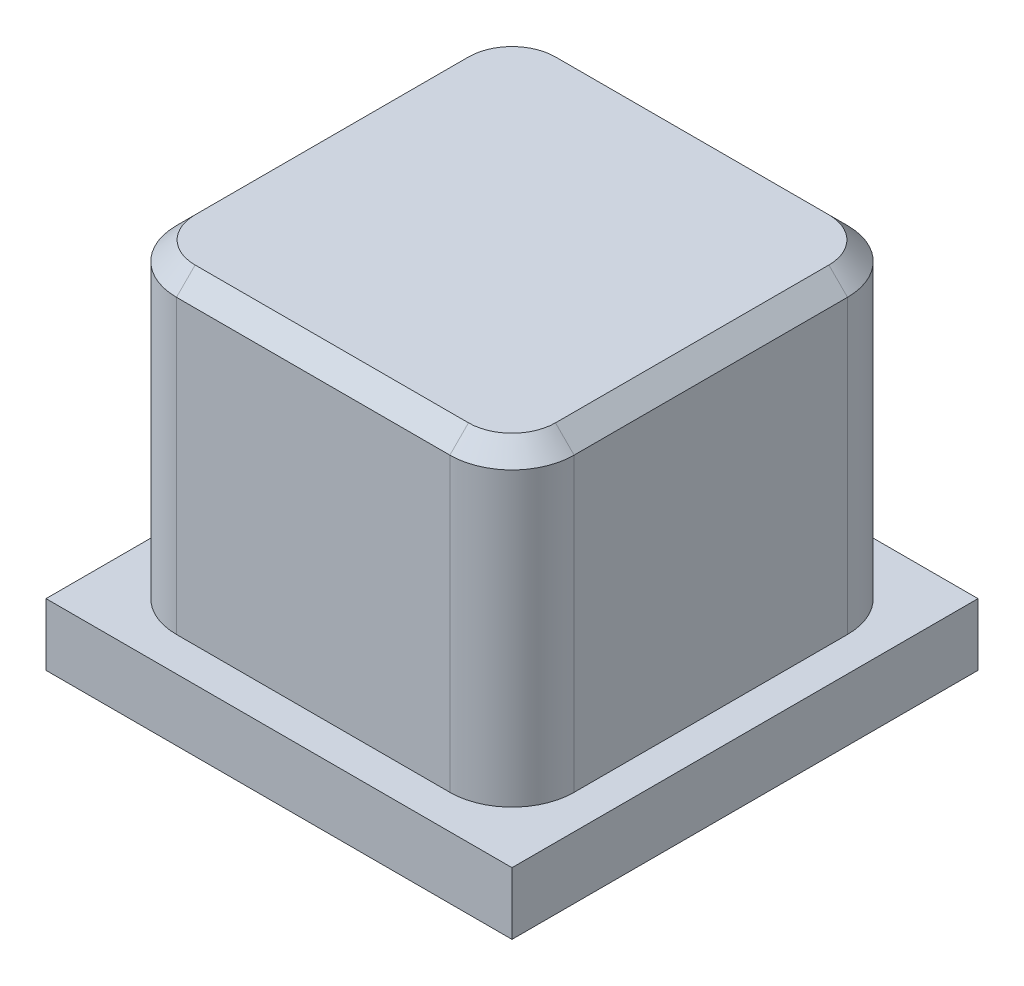
SolidWorks part; units mm, degrees
ref_plane "前视基准面" through (0, 0, 0) normal (0, 0, 1) x (1, 0, 0)
ref_plane "上视基准面" through (0, 0, 0) normal (0, 1, 0) x (1, 0, 0)
ref_plane "右视基准面" through (0, 0, 0) normal (1, 0, 0) x (0, 0, -1)
sketch "草图1" plane through (0, 0, 0) normal (0, 1, 0) x (1, 0, 0)
  line L1 (-7.5, -7.5) -> (7.5, -7.5)
  line L2 (-7.5, -7.5) -> (-7.5, 7.5)
  line L3 (-7.5, 7.5) -> (7.5, 7.5)
  line L4 (7.5, -7.5) -> (7.5, 7.5)
  line L5 (-7.5, -7.5) -> (7.5, 7.5) construction
  line L6 (-7.5, 7.5) -> (7.5, -7.5) construction
  point P0 (0, 0)
  dimension "D1" = 15
extrude "凸台-拉伸1" add sketch "草图1" along normal blind 3
sketch "草图2" plane through (0, 3, 0) normal (0, 1, 0) x (1, 0, 0)
  line L1 (-6.4, -6.4) -> (6.4, -6.4)
  line L2 (-6.4, -6.4) -> (-6.4, 6.4)
  line L3 (-6.4, 6.4) -> (6.4, 6.4)
  line L4 (6.4, -6.4) -> (6.4, 6.4)
  line L5 (-6.4, -6.4) -> (6.4, 6.4) construction
  line L6 (-6.4, 6.4) -> (6.4, -6.4) construction
  point P0 (0, 0)
  dimension "D1" = 12.8
extrude "凸台-拉伸2" add sketch "草图2" along normal blind 10
chamfer "倒角1" distance 1 angle 45 4 edges at (0, 0, -7.5) (-7.5, 0, 0) (0, 0, 7.5) (7.5, 0, 0)
fillet "圆角1" radius 2 4 edges at (6.4, 8, -6.4) (-6.4, 8, -6.4) (-6.4, 8, 6.4) (6.4, 8, 6.4)
chamfer "倒角2" distance 0.6 angle 45 8 edges at (5.8142, 13, 5.8142) (0, 13, 6.4) (-5.8142, 13, 5.8142) (-6.4, 13, 0) (-5.8142, 13, -5.8142) (0, 13, -6.4) (5.8142, 13, -5.8142) (6.4, 13, 0)
